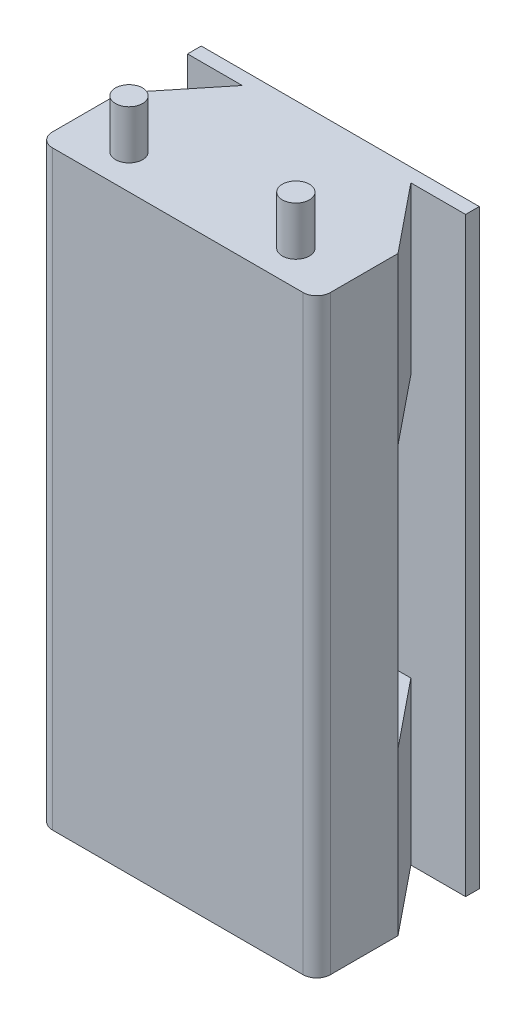
SolidWorks part; units mm, degrees
ref_plane "Front Plane" through (0, 0, 0) normal (0, 0, 1) x (1, 0, 0)
ref_plane "Top Plane" through (0, 0, 0) normal (0, 1, 0) x (1, 0, 0)
ref_plane "Right Plane" through (0, 0, 0) normal (1, 0, 0) x (0, 0, -1)
sketch "Sketch1" plane through (0, 0, 0) normal (0, 1, 0) x (1, 0, 0)
  line L0 (-25.4, 0) -> (76.2, 0)
  line L1 (-25.4, 0) -> (-25.4, 25.4)
  line L2 (-25.4, 25.4) -> (76.2, 25.4)
  line L3 (76.2, 25.4) -> (76.2, 0)
extrude "Boss-Extrude1" add sketch "Sketch1" along normal blind 215.9
sketch "Sketch3" plane through (0, 0, 0) normal (0, -1, 0) x (-1, 0, 0)
  line L0 (-25.4, 25.4) -> (-25.4, 0) construction
  line L1 (5.08, 12.7) -> (-25.4, 12.7) construction
  line L2 (-76.2, 25.4) -> (25.4, 25.4) construction
  line L3 (25.4, 0) -> (-76.2, 0) construction
  line L4 (-25.4, 12.7) -> (-55.88, 12.7) construction
  circle A0 centre (5.08, 12.7) radius 5.207
  circle A1 centre (-55.88, 12.7) radius 5.207
  dimension "D1" = 10.414
  dimension "D2" = 10.414
extrude "Cut-Extrude1" cut sketch "Sketch3" against normal blind 17.78
sketch "Sketch4" plane through (0, 215.9, 0) normal (0, 1, 0) x (1, 0, 0)
  line L0 (25.4, 25.4) -> (25.4, 0) construction
  line L1 (76.2, 25.4) -> (-25.4, 25.4) construction
  line L2 (-25.4, 0) -> (76.2, 0) construction
  line L3 (25.4, 12.7) -> (55.88, 12.7) construction
  line L4 (25.4, 12.7) -> (-5.08, 12.7) construction
  circle A0 centre (-5.08, 12.7) radius 4.953
  circle A1 centre (55.88, 12.7) radius 4.953
  dimension "D1" = 9.906
  dimension "D2" = 9.906
extrude "Boss-Extrude3" add sketch "Sketch4" along normal blind 17.78
sketch "Sketch5" plane through (0, 0, -25.4) normal (0, 0, -1) x (-1, 0, 0)
sketch "Sketch8" plane through (0, 0, -25.4) normal (0, 0, -1) x (-1, 0, 0)
  line L1 (-76.2, 0) -> (25.4, 0)
  line L3 (25.4, 0) -> (25.4, 215.9)
  line L7 (25.4, 215.9) -> (-76.2, 215.9)
  line L8 (-76.2, 215.9) -> (-76.2, 0)
extrude "Boss-Extrude4" add sketch "Sketch8" along normal blind 34
sketch "Sketch10" plane through (0, 215.9, 0) normal (0, 1, 0) x (1, 0, 0)
  line L0 (-25.4, 54.4) -> (-0.4, 54.4) construction
  line L1 (-25.4, 59.4) -> (-25.4, 0) construction
  line L2 (76.2, 54.4) -> (51.2, 54.4) construction
  line L3 (76.2, 0) -> (76.2, 59.4) construction
  line L11 (-14.3379, 59.4) -> (-14.3379, 54.4) construction
  line L12 (67.2647, 59.4) -> (67.2647, 54.4) construction
  line L13 (-25.4, 54.4) -> (-5.4, 54.4)
  line L14 (-5.4, 54.4) -> (-25.4, 29.7)
  line L15 (-25.4, 54.4) -> (-25.4, 29.7)
  line L16 (76.2, 54.4) -> (56.2, 54.4)
  line L17 (56.2, 54.4) -> (76.2, 29.7)
  line L18 (76.2, 54.4) -> (76.2, 29.7)
extrude "Cut-Extrude2" cut sketch "Sketch10" against normal blind 217
sketch "Sketch14" plane through (0, 0, -59.4) normal (0, 0, -1) x (-1, 0, 0)
  line L0 (-76.2, 139.6659) -> (25.4, 139.6659) construction
  line L1 (-25.4, 146.6605) -> (-25.4, 129.6958) construction
  line L2 (-25.4, 129.6958) -> (-9.4, 129.6958) construction
  line L3 (-25.4, 129.6958) -> (-41.4, 129.6958) construction
  line L4 (-41.4, 129.6958) -> (-41.4, 93.6958) construction
  line L5 (-9.4, 129.6958) -> (-9.4, 93.6958) construction
  circle A0 centre (-41.4, 129.6958) radius 3.5
  circle A1 centre (-9.4, 129.6958) radius 3.5
  circle A2 centre (-41.4, 93.6958) radius 3.5
  circle A3 centre (-9.4, 93.6958) radius 3.5
  dimension "D1" = 7
  dimension "D2" = 7
  dimension "7mm" = 7
  dimension "D4" = 7
extrude "Cut-Extrude3" cut sketch "Sketch14" against normal blind 9
fillet "Fillet1" radius 5 1 edges at (-25.4, 107.95, 0)
fillet "Fillet2" radius 5 1 edges at (76.2, 107.95, 0)
sketch "Sketch16" plane through (-25.4, 0, 0) normal (-1, 0, 0) x (0, 0, 1)
  line L4 (-29.7, 158.0129) -> (-29.7, 62.0129)
  line L5 (-29.7, 0) -> (-29.7, 215.9) construction
  line L6 (-29.7, 158.0129) -> (-54.4, 158.0129)
  line L7 (-54.4, 0) -> (-54.4, 215.9) construction
  line L8 (-54.4, 158.0129) -> (-54.4, 62.0129)
  line L9 (-54.4, 62.0129) -> (-29.7, 62.0129)
  line L11 (-54.4, 110.0129) -> (-29.7, 110.0129) construction
  line L12 (-42.05, 110.0129) -> (-42.05, 158.0129) construction
  line L13 (-42.05, 110.0129) -> (-42.05, 62.0129) construction
extrude "Cut-Extrude4" cut sketch "Sketch16" against normal blind 42
sketch "Sketch17" plane through (76.2, 0, 0) normal (1, 0, 0) x (0, 0, -1)
  line L0 (54.4, 155.1993) -> (29.7, 155.1993)
  line L1 (54.4, 0) -> (54.4, 215.9) construction
  line L2 (29.7, 0) -> (29.7, 215.9) construction
  line L3 (29.7, 155.1993) -> (29.7, 59.1993)
  line L4 (29.7, 59.1993) -> (54.4, 59.1993)
  line L5 (54.4, 59.1993) -> (54.4, 155.1993)
  line L6 (54.4, 107.1993) -> (29.7, 107.1993) construction
  line L7 (42.05, 107.1993) -> (42.05, 155.1993) construction
  line L8 (42.05, 107.1993) -> (42.05, 59.1993) construction
  dimension "D1" = 48
extrude "Cut-Extrude5" cut sketch "Sketch17" against normal blind 42
